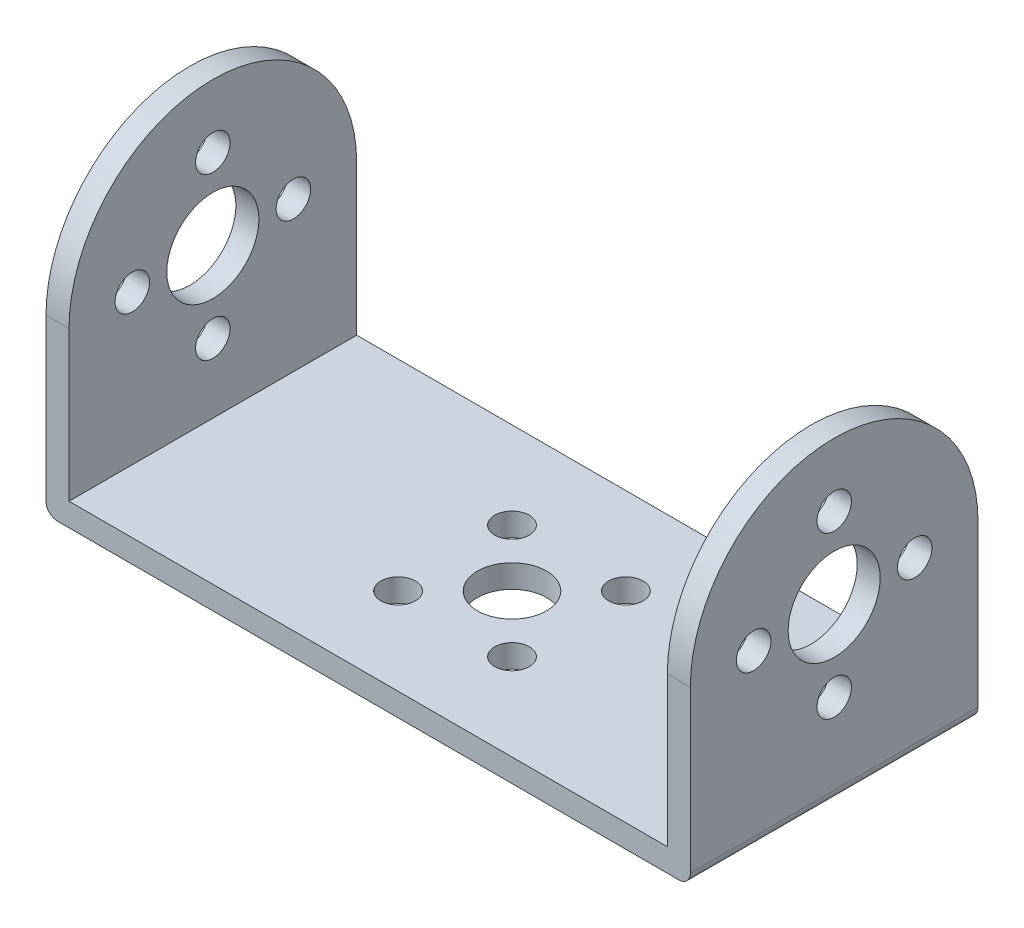
SolidWorks part; units mm, degrees
ref_plane "前视基准面" through (0, 0, 0) normal (0, 0, 1) x (1, 0, 0)
ref_plane "上视基准面" through (0, 0, 0) normal (0, 1, 0) x (1, 0, 0)
ref_plane "右视基准面" through (0, 0, 0) normal (1, 0, 0) x (0, 0, -1)
sketch "草图1" plane through (0, 0, 0) normal (0, 1, 0) x (1, 0, 0)
  line L1 (-20.3457, 13.2314) -> (35.6543, 13.2314)
  line L2 (-20.3457, 13.2314) -> (-20.3457, -11.7686)
  line L3 (-20.3457, -11.7686) -> (35.6543, -11.7686)
  line L4 (35.6543, 13.2314) -> (35.6543, -11.7686)
  dimension "D1" = 25
  dimension "D2" = 56
extrude "凸台-拉伸1" add sketch "草图1" along normal blind 2
sketch "草图2" plane through (0, 2, 0) normal (0, 1, 0) x (1, 0, 0)
  line L0 (7.6543, 13.2314) -> (7.6543, -11.7686) construction
  line L1 (35.6543, 13.2314) -> (-20.3457, 13.2314) construction
  line L2 (-20.3457, -11.7686) -> (35.6543, -11.7686) construction
  line L3 (-20.3457, 0.7314) -> (35.6543, 0.7314) construction
  line L4 (-20.3457, 13.2314) -> (-20.3457, -11.7686) construction
  line L5 (35.6543, -11.7686) -> (35.6543, 13.2314) construction
  circle A0 centre (7.6543, 0.7314) radius 3
  circle A1 centre (7.6543, 0.7314) radius 7 construction
  circle A3 centre (12.604, 5.6811) radius 1.5
  circle A4 centre (2.7045, 5.6811) radius 1.5
  circle A5 centre (12.604, -4.2184) radius 1.5
  circle A6 centre (2.7045, -4.2184) radius 1.5
  point P26 (7.6543, 0.7314)
extrude "切除-拉伸1" cut sketch "草图2" against normal through all
sketch "草图3" plane through (-20.3457, 0, 0) normal (-1, 0, 0) x (0, 0, 1)
  line L0 (-13.2314, 15) -> (-13.2314, 2)
  line L1 (11.7686, 15) -> (11.7686, 2)
  line L2 (-13.2314, 0) -> (11.7686, 0) construction
  line L5 (-13.2314, 2) -> (11.7686, 2)
  arc A0 (11.7686, 15) -> (-13.2314, 15) centre (-0.7314, 15) ccw
  dimension "D4" = 12.5
  dimension "D1" = 15
extrude "凸台-拉伸2" add sketch "草图3" against normal blind 2
sketch "草图4" plane through (-20.3457, 0, 0) normal (-1, 0, 0) x (0, 0, 1)
  line L0 (-13.2314, 15) -> (11.7686, 15) construction
  line L1 (-0.7314, 32) -> (-0.7314, 44.5) construction
  circle A1 centre (-0.7314, 15) radius 4
  circle A2 centre (-0.7314, 22) radius 1.5
  circle A3 centre (6.2686, 15) radius 1.5
  circle A4 centre (-0.7314, 8) radius 1.5
  circle A5 centre (-7.7314, 15) radius 1.5
  point P21 (-0.7314, 15)
  dimension "D1" = 7
  dimension "D2" = 4
extrude "切除-拉伸2" cut sketch "草图4" against normal up to next
ref_plane "基准面1" through (7.6543, 0, 0) normal (-1, 0, 0) x (0, 0, 1)
mirror "镜向1" about plane through (7.6543, 0, 0) normal (-1, 0, 0) of "切除-拉伸2", "凸台-拉伸2"
fillet "圆角1" radius 1 2 edges at (35.6543, 0, -0.7314) (-20.3457, 0, -0.7314)
